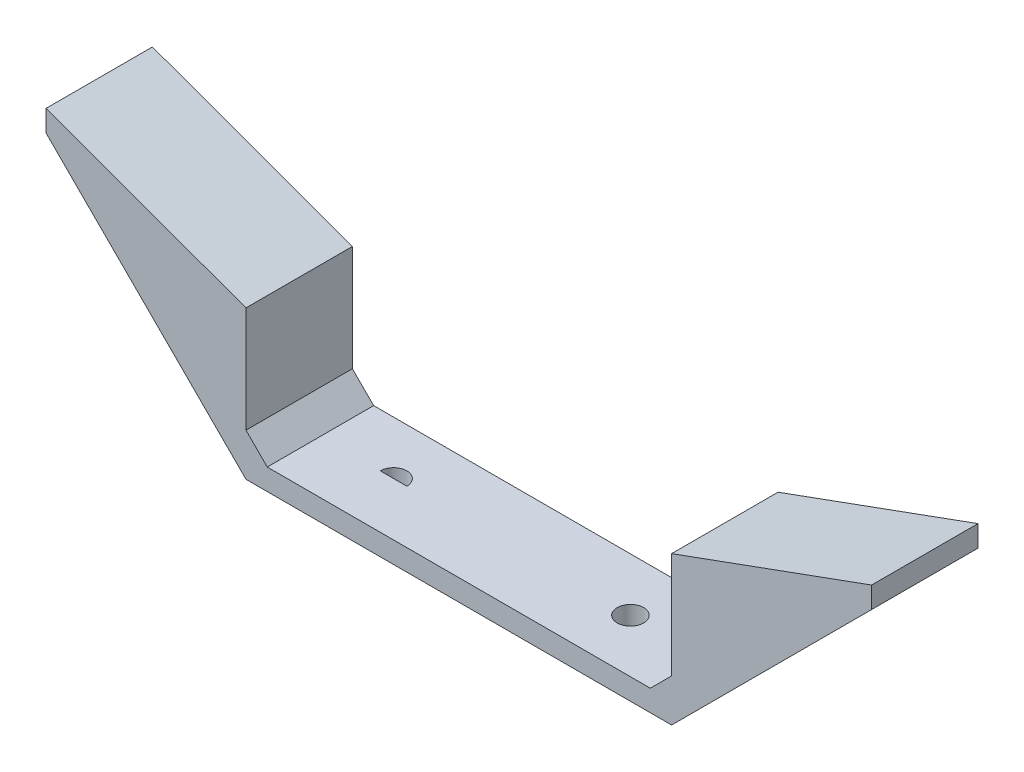
SolidWorks part; units mm, degrees
ref_plane "Front Plane" through (0, 0, 0) normal (0, 0, 1) x (1, 0, 0)
ref_plane "Top Plane" through (0, 0, 0) normal (0, 1, 0) x (1, 0, 0)
ref_plane "Right Plane" through (0, 0, 0) normal (1, 0, 0) x (0, 0, -1)
sketch "Sketch1" plane through (0, 0, 0) normal (0, 0, 1) x (1, 0, 0)
  line L0 (25.4, 0) -> (49.2682, 23.8682)
  line L1 (0, 0) -> (25.4, 0)
  line L2 (0, 0) -> (0, 2.54)
  line L3 (0, 2.54) -> (22.86, 2.54)
  line L4 (25.4, 0) -> (25.4, 2.54) construction
  line L5 (49.2682, 23.8682) -> (49.2682, 26.4082)
  line L6 (25.4, 5.08) -> (25.4, 17.7209)
  line L7 (25.4, 17.7209) -> (49.2682, 26.4082)
  line L8 (49.2903, 26.4082) -> (46.1412, 26.4082) construction
  line L9 (22.86, 2.54) -> (25.4, 5.08)
  dimension "D1" = 2.54
  dimension "D2" = 25.4
  dimension "D3" = 45
  dimension "D4" = 2.54
  dimension "D5" = 20
  dimension "D6" = 25.4
extrude "Boss-Extrude1" add sketch "Sketch1" along normal blind 12.7
mirror "Mirror1" about plane through (0, 0, 12.7) normal (1, 0, 0) of "Boss-Extrude1"
sketch "Sketch2" plane through (0, 2.54, 0) normal (0, 1, 0) x (1, 0, 0)
  line L0 (-17.7757, -6.35) -> (-10.5, -6.35)
  line L1 (-14.1379, -6.35) -> (14.1379, -6.35) construction
  line L2 (22.86, 0) -> (-22.86, 0) construction
  line L3 (22.86, -12.7) -> (22.86, 0) construction
  line L4 (-17.7757, -17.78) -> (-17.7757, 5.08) construction
  line L5 (-10.5, 1.9699) -> (-10.5, 2.9101) construction
  circle A0 centre (-14.1379, -6.35) radius 1.5875
  circle A1 centre (14.1379, -6.35) radius 1.5875
  point P4 (0, 0)
  point P5 (0, -6.35)
  point P8 (0, 0)
  point P12 (22.86, -6.35)
  point P16 (0, 0)
  point P19 (0, 0)
  point P20 (-14.1379, -6.35)
  dimension "D2" = 3.175
extrude "Cut-Extrude1" cut sketch "Sketch2" against normal up to next
